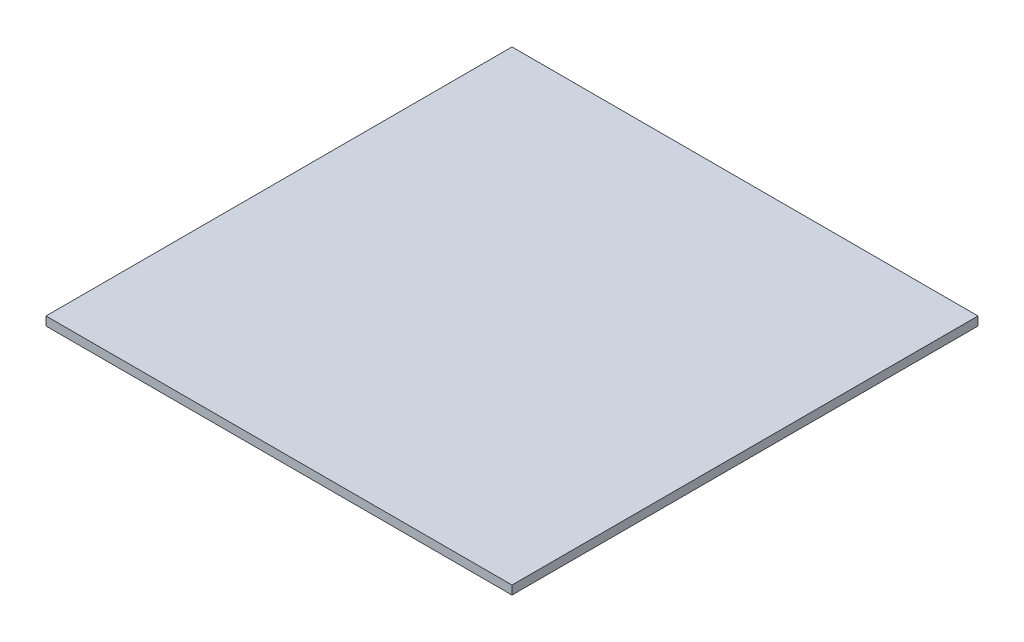
SolidWorks part; units mm, degrees
material "FR-4"
ref_plane "Спереди" through (0, 0, 0) normal (0, 0, 1) x (1, 0, 0)
ref_plane "Сверху" through (0, 0, 0) normal (0, 1, 0) x (1, 0, 0)
ref_plane "Справа" through (0, 0, 0) normal (1, 0, 0) x (0, 0, -1)
other "Configuration Table"
sketch "Эскиз1" plane through (0, 0, 0) normal (0, 1, 0) x (1, 0, 0)
  line L1 (0, 80) -> (80, 80)
  line L2 (0, 80) -> (0, 0)
  line L3 (0, 0) -> (80, 0)
  line L4 (80, 80) -> (80, 0)
  dimension "D1" = 80
  dimension "D2" = 80
extrude "Бобышка-Вытянуть1" add sketch "Эскиз1" along normal blind 1.5
